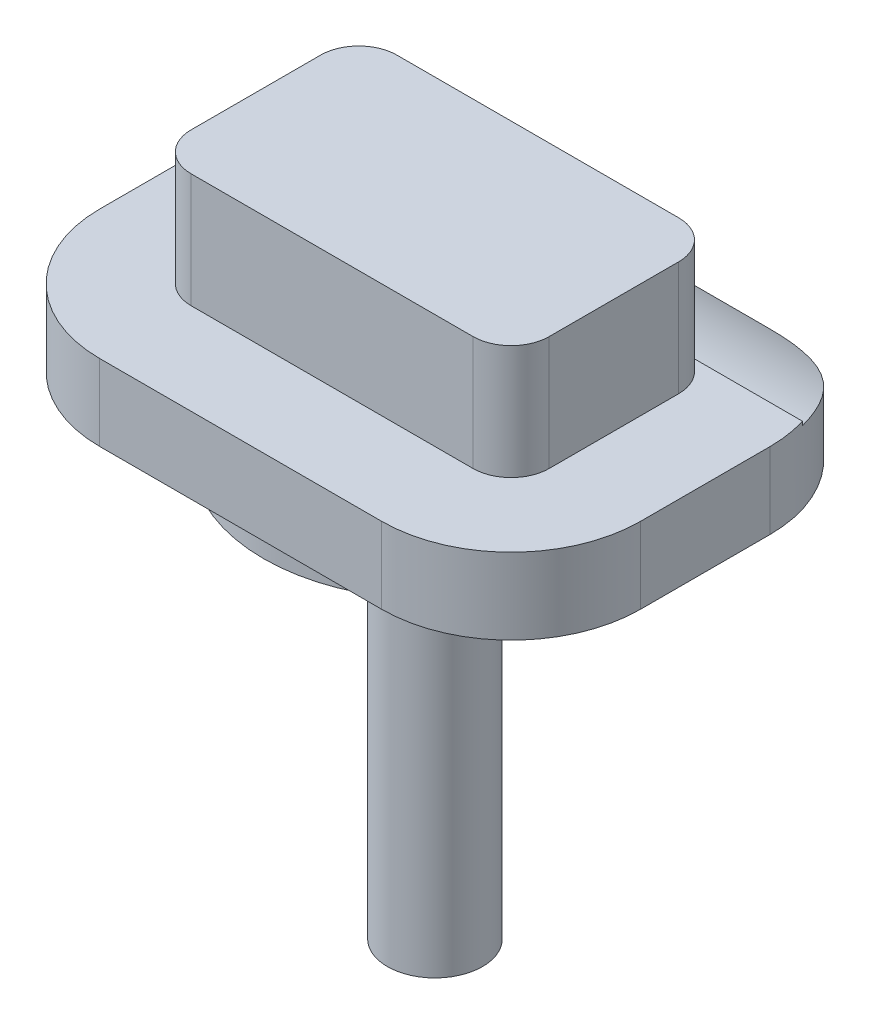
SolidWorks part; units mm, degrees
ref_plane "Front Plane" through (0, 0, 0) normal (0, 0, 1) x (1, 0, 0)
ref_plane "Top Plane" through (0, 0, 0) normal (0, 1, 0) x (1, 0, 0)
ref_plane "Right Plane" through (0, 0, 0) normal (1, 0, 0) x (0, 0, -1)
sketch "Sketch1" plane through (0, 0, 0) normal (0, 1, 0) x (1, 0, 0)
  line L1 (1, 0) -> (8.4, 0)
  line L2 (0, 1) -> (0, 4.4)
  line L3 (1, 5.4) -> (8.4, 5.4)
  line L4 (9.4, 1) -> (9.4, 4.4)
  arc A0 (8.4, 5.4) -> (9.4, 4.4) centre (8.4, 4.4) cw
  arc A1 (9.4, 1) -> (8.4, 0) centre (8.4, 1) cw
  arc A2 (1, 0) -> (0, 1) centre (1, 1) cw
  arc A3 (0, 4.4) -> (1, 5.4) centre (1, 4.4) cw
  point P9 (9.4, 0)
  point P12 (0, 0)
  point P15 (0, 5.4)
  dimension "D3" = 1
  dimension "D1" = 9.4
  dimension "D2" = 5.4
extrude "Boss-Extrude1" add sketch "Sketch1" along normal blind 3
sketch "Sketch2" plane through (0, 0, 0) normal (0, -1, 0) x (1, 0, 0)
  line L1 (1, -7.8) -> (8.4, -7.8)
  line L2 (-2.4, -4.4) -> (-2.4, -1)
  line L3 (1, 2.4) -> (8.4, 2.4)
  line L4 (11.8, -4.4) -> (11.8, -1)
  line L5 (8.4, -5.4) -> (8.4, -7.8) construction
  line L6 (8.4, 0) -> (8.4, 2.4) construction
  line L7 (0, -4.4) -> (-2.4, -4.4) construction
  line L8 (9.4, -4.4) -> (11.8, -4.4) construction
  line L9 (0, -4.4) -> (0, -1) construction
  line L10 (1, 0) -> (8.4, 0) construction
  line L11 (9.4, -1) -> (9.4, -4.4) construction
  line L12 (8.4, -5.4) -> (1, -5.4) construction
  arc A0 (1, 2.4) -> (-2.4, -1) centre (1, -1) ccw
  arc A1 (8.4, 2.4) -> (11.8, -1) centre (8.4, -1) cw
  arc A2 (11.8, -4.4) -> (8.4, -7.8) centre (8.4, -4.4) cw
  arc A3 (1, -7.8) -> (-2.4, -4.4) centre (1, -4.4) cw
  arc A5 (0, -4.4) -> (1, -5.4) centre (1, -4.4) ccw construction
  arc A6 (1, 0) -> (0, -1) centre (1, -1) ccw construction
  dimension "D2" = 3.4
  dimension "D1" = 2.4
extrude "Boss-Extrude2" add sketch "Sketch2" along normal blind 2
sketch "Sketch3" plane through (-2.4, 0, 0) normal (-1, 0, 0) x (0, 0, 1)
  line L0 (-5.4, -0.1) -> (-5.4, 0.4)
  line L1 (-5.4, 0.4) -> (-7.8, 0.4)
  line L2 (-7.8, 0.4) -> (-7.8, -0.73)
  line L3 (-5.4, 3) -> (-5.4, 0) construction
  line L4 (-7.8, -2) -> (-7.8, 0) construction
  line L5 (-4.4, 0) -> (-1, 0) construction
  arc A0 (-7.8, -0.73) -> (-5.4, -0.1) centre (-5.0577, -6.2905) cw
  dimension "D1" = 6.2
  dimension "D2" = 0.5
  dimension "D3" = 1.13
  dimension "D4" = 0.4
extrude "Cut-Extrude1" cut sketch "Sketch3" against normal through all
sketch "Sketch6" plane through (0, -2, 0) normal (0, -1, 0) x (1, 0, 0)
  line L0 (-2.4, -2.7) -> (11.8, -2.7) construction
  line L1 (-2.4, -1) -> (-2.4, -4.4) construction
  line L2 (11.8, -4.4) -> (11.8, -1) construction
  line L3 (4.7, -2.7) -> (4.7, 2.4) construction
  line L4 (8.4, 2.4) -> (1, 2.4) construction
  circle A0 centre (4.7, -2.7) radius 2.65
  circle A1 centre (4.7, -2.7) radius 3.5
  dimension "D1" = 5.3
  dimension "D2" = 7
extrude "Cut-Extrude3" cut sketch "Sketch6" against normal blind 1
sketch "Sketch7" plane through (0, -2, 0) normal (0, -1, 0) x (1, 0, 0)
  circle A0 centre (4.7, -2.7) radius 2.65
  circle A1 centre (4.7, -2.7) radius 2.65 construction
extrude "Boss-Extrude4" add sketch "Sketch7" along normal blind 1
sketch "Sketch8" plane through (0, -2, 0) normal (0, -1, 0) x (1, 0, 0)
  circle A0 centre (4.7, -2.7) radius 4.5
  circle A1 centre (4.7, -2.7) radius 3.5 construction
  circle A2 centre (4.7, -2.7) radius 3.5
  dimension "D1" = 1
extrude "Boss-Extrude5" add sketch "Sketch8" along normal blind 1
sketch "Sketch9" plane through (0, -3, 0) normal (0, -1, 0) x (1, 0, 0)
  circle A0 centre (4.7, -2.7) radius 1.25
  circle A1 centre (4.7, -2.7) radius 1.65 construction
  dimension "D1" = 2.5
extrude "Boss-Extrude6" add sketch "Sketch9" along normal up to surface (10.9 mm away)
chamfer "Chamfer2" distance 1 angle 45 1 edges at (4.7, -3, -3.95)
